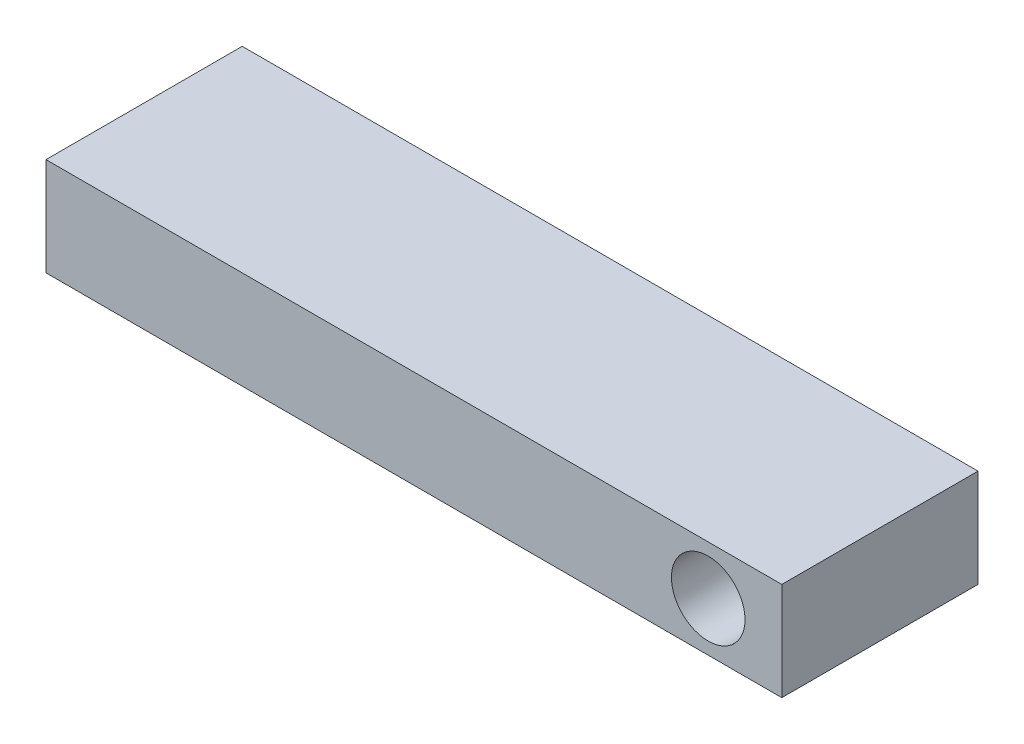
SolidWorks part; units mm, degrees
ref_plane "Front Plane" through (0, 0, 0) normal (0, 0, 1) x (1, 0, 0)
ref_plane "Top Plane" through (0, 0, 0) normal (0, 1, 0) x (1, 0, 0)
ref_plane "Right Plane" through (0, 0, 0) normal (1, 0, 0) x (0, 0, -1)
sketch "Sketch1" plane through (0, 0, 0) normal (0, 0, 1) x (1, 0, 0)
  line L0 (0, 0) -> (0, 12.7)
  line L1 (95.25, 0) -> (95.25, 12.7)
  line L2 (95.25, 0) -> (0, 0)
  line L3 (95.25, 12.7) -> (0, 12.7)
  circle A0 centre (85.725, 6.35) radius 4.7625
  point P6 (95.25, 6.35)
  dimension "D4" = 9.525
  dimension "D1" = 95.25
  dimension "D2" = 12.7
  dimension "D6" = 85.725
extrude "Boss-Extrude1" add sketch "Sketch1" along normal blind 25.4
